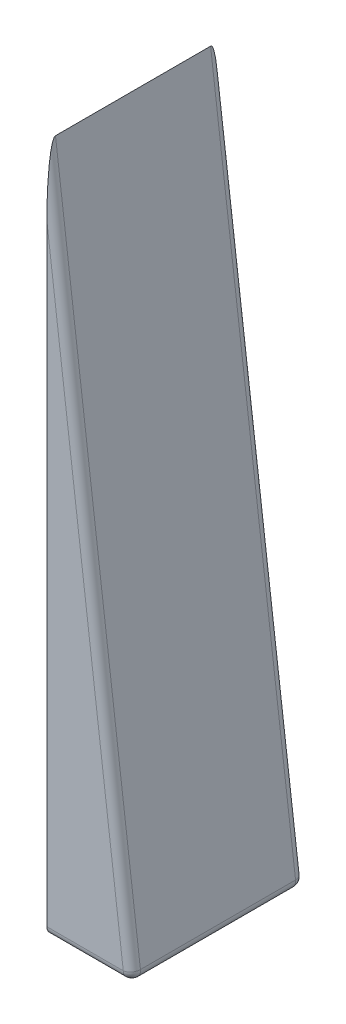
SolidWorks part; units mm, degrees
ref_plane "Front Plane" through (0, 0, 0) normal (0, 0, 1) x (1, 0, 0)
ref_plane "Top Plane" through (0, 0, 0) normal (0, 1, 0) x (1, 0, 0)
ref_plane "Right Plane" through (0, 0, 0) normal (1, 0, 0) x (0, 0, -1)
sketch "Sketch1" plane through (0, 0, 0) normal (0, 1, 0) x (1, 0, 0)
  line L1 (-6.35, -12.7) -> (6.35, -12.7)
  line L2 (-6.35, -12.7) -> (-6.35, 12.7)
  line L3 (-6.35, 12.7) -> (6.35, 12.7)
  line L4 (6.35, -12.7) -> (6.35, 12.7)
  line L5 (-6.35, -12.7) -> (6.35, 12.7) construction
  line L6 (-6.35, 12.7) -> (6.35, -12.7) construction
  point P0 (0, 0)
  dimension "D1" = 12.7
  dimension "D2" = 25.4
extrude "Boss-Extrude1" add sketch "Sketch1" along normal blind 101.6
sketch "Sketch2" plane through (0, 0, 12.7) normal (0, 0, 1) x (1, 0, 0)
  line L0 (6.35, 0) -> (-6.35, 101.6)
  line L1 (-6.35, 101.6) -> (6.35, 101.6)
  line L2 (6.35, 101.6) -> (6.35, 0)
extrude "Cut-Extrude1" cut sketch "Sketch2" against normal through all
fillet "Fillet1" radius 1.27 5 edges at (0, 0, -12.7) (0, 50.8, -12.7) (0, 0, 12.7) (6.35, 0, 0) (0, 50.8, 12.7)
